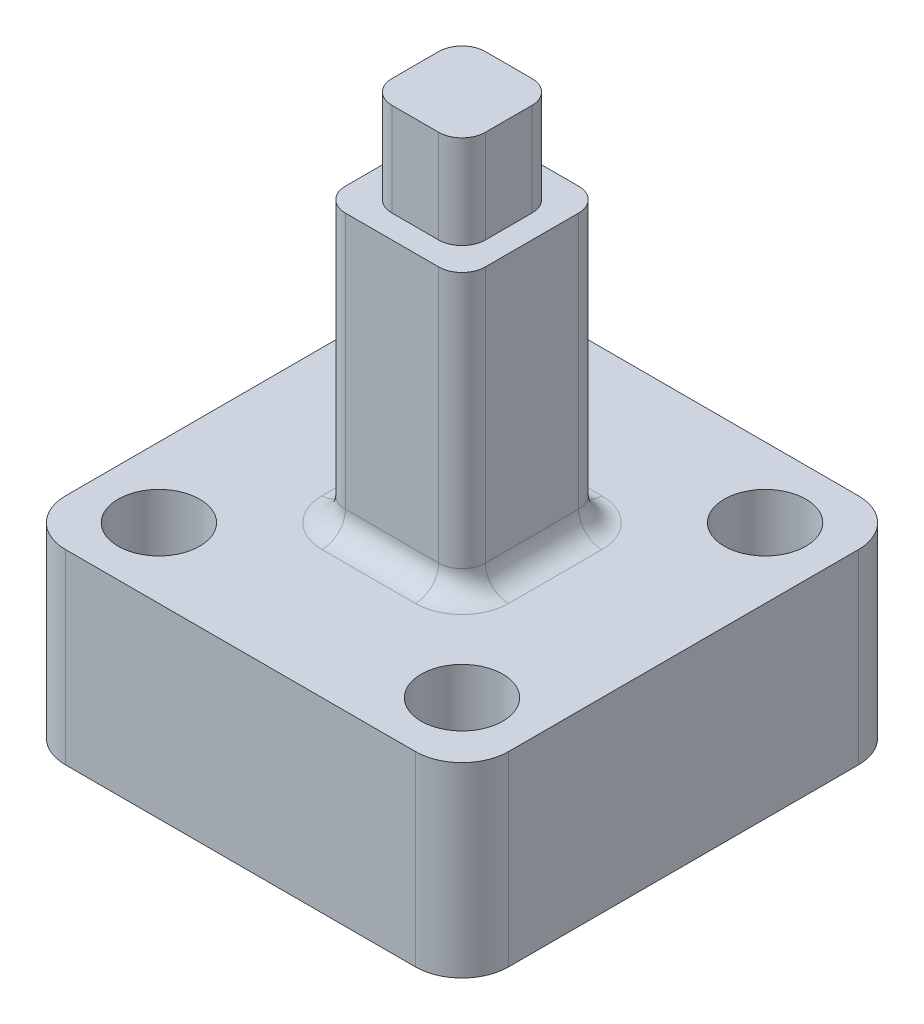
SolidWorks part; units mm, degrees
ref_plane "Front Plane" through (0, 0, 0) normal (0, 0, 1) x (1, 0, 0)
ref_plane "Top Plane" through (0, 0, 0) normal (0, 1, 0) x (1, 0, 0)
ref_plane "Right Plane" through (0, 0, 0) normal (1, 0, 0) x (0, 0, -1)
sketch "Sketch1" plane through (0, 0, 0) normal (0, 1, 0) x (1, 0, 0)
  line L1 (9.5, -9.5) -> (-9.5, -9.5)
  line L2 (9.5, -9.5) -> (9.5, 9.5)
  line L3 (9.5, 9.5) -> (-9.5, 9.5)
  line L4 (-9.5, -9.5) -> (-9.5, 9.5)
  line L5 (9.5, -9.5) -> (-9.5, 9.5) construction
  line L6 (9.5, 9.5) -> (-9.5, -9.5) construction
  point P0 (0, 0)
  dimension "D1" = 19
  dimension "D2" = 19
extrude "Boss-Extrude1" add sketch "Sketch1" along normal blind 8
sketch "Sketch2" plane through (0, 8, 0) normal (0, 1, 0) x (1, 0, 0)
  line L1 (6.5, -6.5) -> (-6.5, -6.5) construction
  line L2 (6.5, -6.5) -> (6.5, 6.5) construction
  line L3 (6.5, 6.5) -> (-6.5, 6.5) construction
  line L4 (-6.5, -6.5) -> (-6.5, 6.5) construction
  line L5 (6.5, -6.5) -> (-6.5, 6.5) construction
  line L6 (6.5, 6.5) -> (-6.5, -6.5) construction
  circle A0 centre (-6.5, 6.5) radius 1.75
  circle A1 centre (6.5, 6.5) radius 1.75
  circle A2 centre (-6.5, -6.5) radius 1.75
  circle A3 centre (6.5, -6.5) radius 1.75
  point P0 (0, 0)
  dimension "D3" = 3.5
  dimension "D1" = 13
  dimension "D2" = 13
extrude "Cut-Extrude1" cut sketch "Sketch2" against normal through all
sketch "Sketch3" plane through (0, 8, 0) normal (0, 1, 0) x (1, 0, 0)
  line L1 (3, -3) -> (-3, -3)
  line L2 (3, -3) -> (3, 3)
  line L3 (3, 3) -> (-3, 3)
  line L4 (-3, -3) -> (-3, 3)
  line L5 (3, -3) -> (-3, 3) construction
  line L6 (3, 3) -> (-3, -3) construction
  point P0 (0, 0)
  dimension "D1" = 6
  dimension "D2" = 6
extrude "Boss-Extrude2" add sketch "Sketch3" along normal blind 12
fillet "Fillet1" radius 2 4 edges at (9.5, 4, 9.5) (9.5, 4, -9.5) (-9.5, 4, 9.5) (-9.5, 4, -9.5)
sketch "Sketch5" plane through (0, 20, 0) normal (0, 1, 0) x (1, 0, 0)
  line L1 (2, -2) -> (-2, -2)
  line L2 (2, -2) -> (2, 2)
  line L3 (2, 2) -> (-2, 2)
  line L4 (-2, -2) -> (-2, 2)
  line L5 (2, -2) -> (-2, 2) construction
  line L6 (2, 2) -> (-2, -2) construction
  point P0 (0, 0)
  dimension "D1" = 4
  dimension "D2" = 4
extrude "Boss-Extrude4" add sketch "Sketch5" along normal blind 4
fillet "Fillet3" radius 1 12 edges at (0, 8, -3) (-3, 8, 0) (3, 8, 0) (0, 8, 3) (2, 22, -2) (-2, 22, -2) (-2, 22, 2) (2, 22, 2) (3, 14, 3) (-3, 14, 3) (-3, 14, -3) (3, 14, -3)
